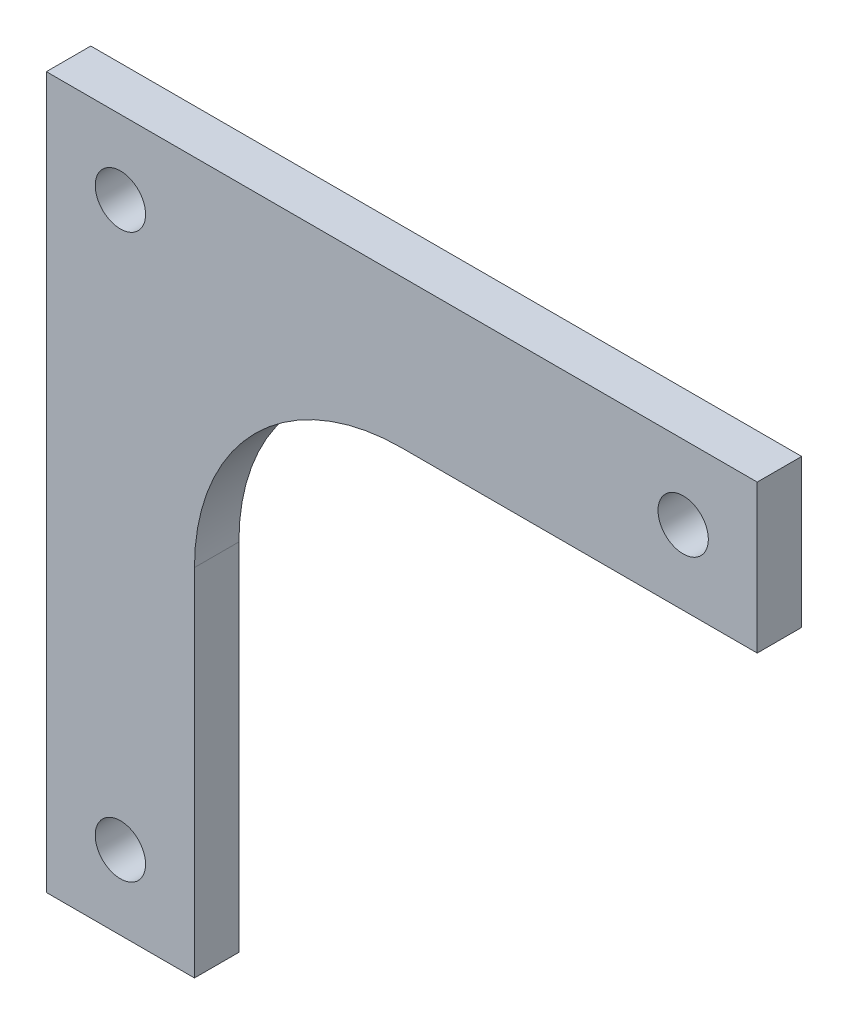
SolidWorks part; units mm, degrees
ref_plane "前视基准面" through (0, 0, 0) normal (0, 0, 1) x (1, 0, 0)
ref_plane "上视基准面" through (0, 0, 0) normal (0, 1, 0) x (1, 0, 0)
ref_plane "右视基准面" through (0, 0, 0) normal (1, 0, 0) x (0, 0, -1)
sketch "草图1" plane through (0, 0, 0) normal (0, 0, 1) x (1, 0, 0)
  line L0 (0, 0) -> (0, 24)
  line L1 (0, 24) -> (24, 24)
  line L2 (24, 24) -> (24, 14) construction
  line L3 (24, 14) -> (10, 14) construction
  line L4 (10, 14) -> (10, 0) construction
  line L5 (10, 0) -> (0, 0) construction
  line L6 (0, 0) -> (0, -14)
  line L8 (24, 24) -> (38, 24)
  line L10 (34, 14) -> (10, 14) construction
  line L11 (10, 14) -> (10, -12) construction
  line L12 (10, 0) -> (10, -12)
  line L13 (24, 14) -> (34, 14)
  line L14 (10, -12) -> (10, -24)
  line L15 (10, -24) -> (0, -24)
  line L16 (0, -24) -> (0, -14)
  line L17 (38, 24) -> (48, 24)
  line L18 (48, 24) -> (48, 14)
  line L19 (48, 14) -> (34, 14)
  line L20 (0, -14) -> (38, -14) construction
  line L21 (38, -14) -> (38, 24) construction
  arc A0 (24, 14) -> (10, 0) centre (24, 0) ccw
  circle A1 centre (43, 19) radius 1.7
  circle A2 centre (5, -19) radius 1.7
  circle A3 centre (5, 19) radius 1.7
  circle A4 centre (24, 0) radius 14 construction
  point P20 (0, -19)
  point P21 (5, -24)
  point P22 (43, 24)
  point P23 (48, 19)
  dimension "D5" = 3.4
  dimension "D6" = 3.4
  dimension "D1" = 10
  dimension "D2" = 24
  dimension "D3" = 48
  dimension "D4" = 48
  dimension "D7" = 14
  dimension "D8" = 14
  dimension "D9" = 5
  dimension "D10" = 5
  dimension "D11" = 5
  dimension "D12" = 5
  dimension "D13" = 5
  dimension "D14" = 5
extrude "凸台-拉伸1" add sketch "草图1" along normal blind 3
